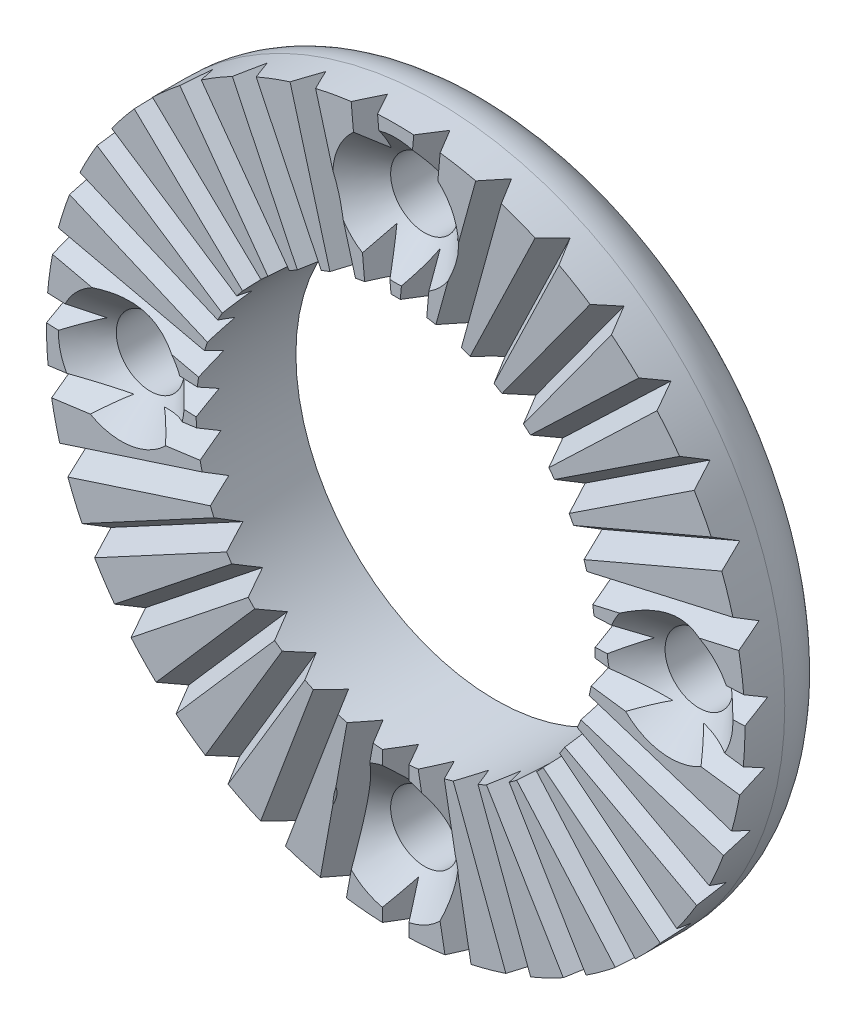
SolidWorks part; units mm, degrees
material "Alumina"
ref_plane "Plano frontal" through (0, 0, 0) normal (0, 0, 1) x (1, 0, 0)
ref_plane "Plano superior" through (0, 0, 0) normal (0, 1, 0) x (1, 0, 0)
ref_plane "Plano direito" through (0, 0, 0) normal (1, 0, 0) x (0, 0, -1)
sketch "Esboço1" plane through (0, 0, 0) normal (0, 0, 1) x (1, 0, 0)
  circle A0 centre (0, 0) radius 17.5
  dimension "D1" = 35
extrude "Ressalto-extrusão1" add sketch "Esboço1" along normal blind 5
fillet "Filete1" radius 3 1 edges at (17.5, 0, 0)
sketch "Esboço2" plane through (0, 0, 0) normal (0, 1, 0) x (1, 0, 0)
  line L0 (-17.5, -5) -> (17.5, -5) construction
  line L1 (-0.9959, -5.575) -> (0.9959, -5.575)
  line L2 (0.9959, -5.575) -> (0, -3.85)
  line L3 (0, -3.85) -> (-0.9959, -5.575)
  circle A0 centre (0, -5) radius 0.575 construction
  dimension "D1" = 1.15
extrude "Corte-extrusão1" cut sketch "Esboço2" against normal through all
pattern_circular "PadrãoCircular1" count 35 over 360 about axis through (0, 0, 0) along (0, 0, 1) of "Corte-extrusão1"
sketch "Esboço3" plane through (0, 0, 0) normal (0, 0, -1) x (-1, 0, 0)
  circle A0 centre (0, 0) radius 10
  dimension "D1" = 20
extrude "Corte-extrusão2" cut sketch "Esboço3" against normal through all
hole_wizard "Escareado para parafuso com cabeça escareada elevada de M31" positions "Esboço6" profile "Esboço7" countersink size "M3" standard "DIN"
sketch "Esboço6" plane through (0, 0, 5) normal (0, 0, 1) x (1, 0, 0)
  point P0 (0, 13.75)
  dimension "D1" = 13.75
sketch "Esboço7" plane through (0, 13.75, 5) normal (1, 0, 0) x (0, -1, 0)
  line L0 (0, 0) -> (0, 73.7715)
  line L1 (0, 73.7715) -> (1.7, 72.75)
  line L2 (1.7, 72.75) -> (1.7, 1.45)
  line L3 (1.7, 1.45) -> (3.15, 0)
  line L5 (3.15, 0) -> (0, 0)
  line L6 (-1.7, 1.45) -> (-3.15, 0) construction
  line L10 (0, 73.7715) -> (-1.7, 72.75) construction
  line L11 (0, -6.35) -> (0, 107.95) construction
  dimension "Hole Dia." = 3.4
  dimension "Hole Depth" = 72.75
  dimension "Near C'Sink Dia." = 6.3
  dimension "Near C'Sink Angle" = 90
  dimension "Drill Angle" = 118
pattern_circular "PadrãoCircular2" count 4 over 360 about axis through (0, 0, 0) along (0, 0, 1) of "Escareado para parafuso com cabeça escareada elevada de M31"
